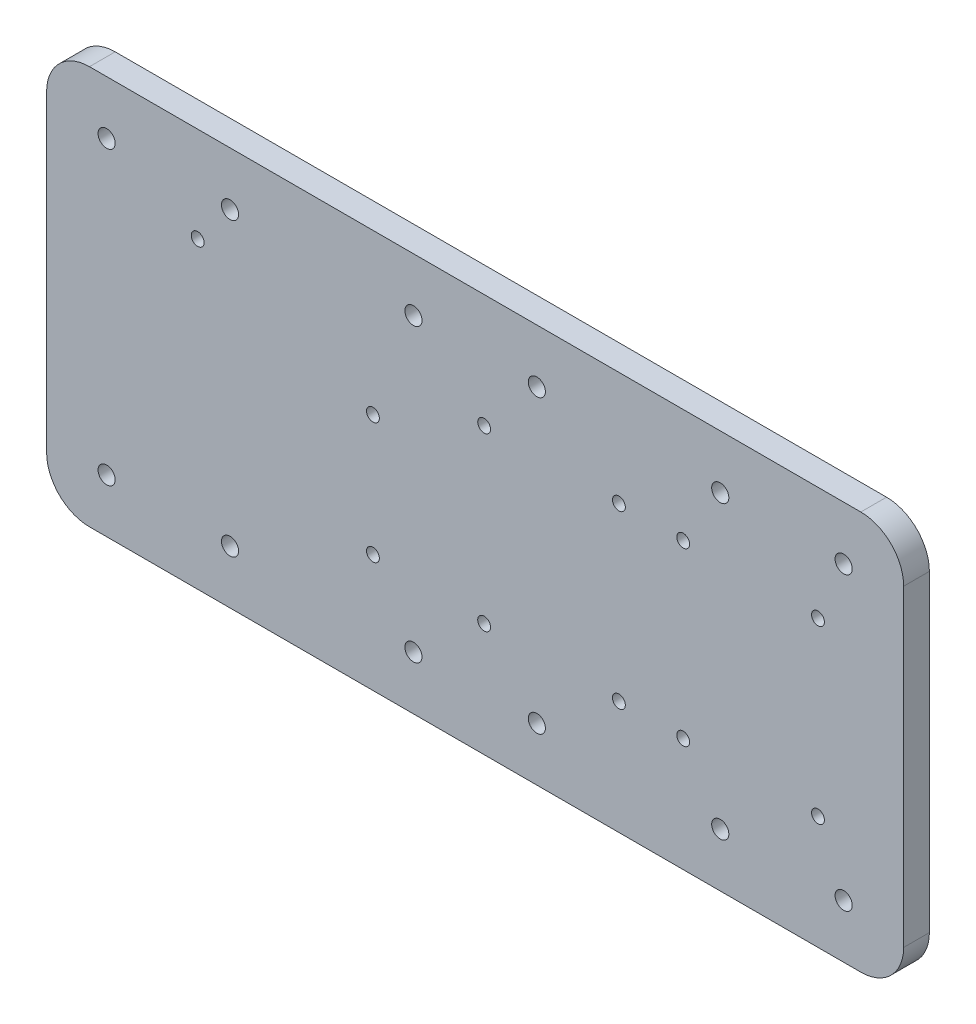
SolidWorks part; units mm, degrees
ref_plane "前基準面" through (0, 0, 0) normal (0, 0, 1) x (1, 0, 0)
ref_plane "上基準面" through (0, 0, 0) normal (0, 1, 0) x (1, 0, 0)
ref_plane "右基準面" through (0, 0, 0) normal (1, 0, 0) x (0, 0, -1)
sketch "草圖1" plane through (0, 0, 0) normal (0, 0, 1) x (1, 0, 0)
  line L0 (-200, 60) -> (-200, 76.5)
  line L1 (-200, 76.5) -> (-168.2, 76.5)
  line L2 (0, 0) -> (0, 60)
  line L3 (-125.9, 76.5) -> (-94.1, 76.5)
  line L4 (-200, 0) -> (-200, 60)
  line L5 (-51.8, 76.5) -> (0, 76.5)
  line L6 (0, 76.5) -> (0, 60)
  line L7 (0, 0) -> (0, -16.5)
  line L8 (0, -16.5) -> (-51.8, -16.5)
  line L9 (-200, 0) -> (-200, -16.5)
  line L10 (-200, -16.5) -> (-168.2, -16.5)
  line L11 (-125.9, -16.5) -> (-94.1, -16.5)
  line L24 (-168.2, 76.5) -> (-125.9, 76.5)
  line L31 (-168.2, -16.5) -> (-125.9, -16.5)
  line L35 (-94.1, 76.5) -> (-51.8, 76.5)
  line L37 (-94.1, -16.5) -> (-51.8, -16.5)
  dimension "D1" = 200
  dimension "D2" = 60
  dimension "D6" = 31.8
extrude "填料-伸長1" add sketch "草圖1" along normal blind 6
ref_plane "平面1" through (0, 0, -35.9) normal (0, 0, 1) x (1, 0, 0)
sketch "草圖10" plane through (0, 0, 6) normal (0, 0, 1) x (1, 0, 0)
  line L0 (-200, 76.5) -> (-200, -16.5) construction
  circle A0 centre (-164.75, 54.3) radius 1.5
  circle A1 centre (-123.85, 39.25) radius 1.5
  circle A2 centre (-123.85, 10.975) radius 1.5
  circle A7 centre (-97.9, 50) radius 1.5
  circle A9 centre (-66.45, 50) radius 1.5
  circle A11 centre (-51.45, 50) radius 1.5
  circle A13 centre (-20, 50) radius 1.5
  circle A15 centre (-20, 10) radius 1.5
  circle A17 centre (-51.45, 10) radius 1.5
  circle A19 centre (-66.45, 10) radius 1.5
  circle A21 centre (-97.9, 10) radius 1.5
  point P2 (-174.75, 54.3)
  dimension "D6" = 3
  dimension "D1" = 35.25
extrude "除料-伸長1" cut sketch "草圖10" against normal up to surface (6 mm away) up to face at (-100, 30, 0)
sketch "草圖11" plane through (0, 0, 6) normal (0, 0, 1) x (1, 0, 0)
  line L2 (0, 76.5) -> (-200, 76.5) construction
  line L3 (0, -16.5) -> (0, 76.5) construction
  circle A0 centre (-14, 64) radius 2
  circle A1 centre (-42.8, 64) radius 2
  circle A2 centre (-85.6, 64) radius 2
  circle A3 centre (-114.4, 64) radius 2
  circle A4 centre (-157.2, 64) radius 2
  circle A5 centre (-186, 64) radius 2
  circle A6 centre (-14, -4) radius 2
  circle A7 centre (-42.8, -4) radius 2
  circle A8 centre (-85.6, -4) radius 2
  circle A9 centre (-114.4, -4) radius 2
  circle A10 centre (-157.2, -4) radius 2
  circle A11 centre (-186, -4) radius 2
  dimension "D1" = 12.5
  dimension "D2" = 14
  dimension "D3" = 12.5
  dimension "D4" = 28.8
  dimension "D5" = 3
  dimension "D6" = 4
  dimension "D8" = 4
  dimension "D7" = 2
extrude "除料-伸長2" cut sketch "草圖11" against normal up to next
fillet "圓角1" radius 10 4 edges at (-200, -16.5, 3) (0, -16.5, 3) (0, 76.5, 3) (-200, 76.5, 3)
